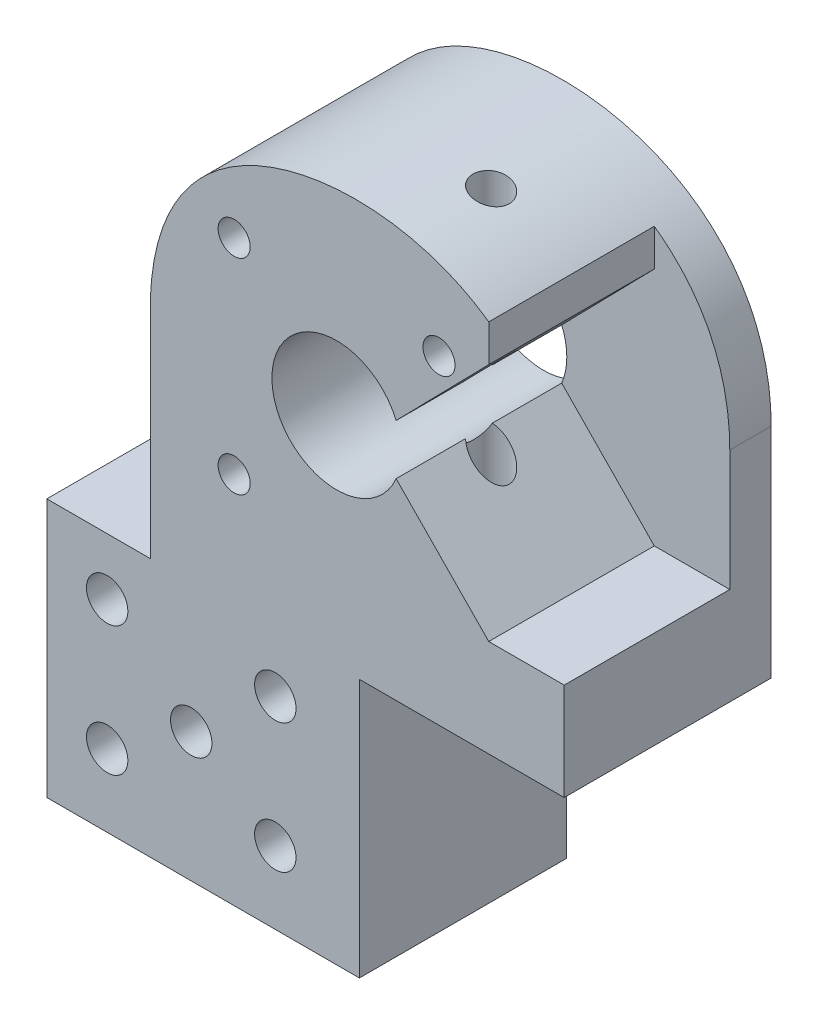
SolidWorks part; units mm, degrees
material "6061-T4 (SS)"
ref_plane "Piano frontale" through (0, 0, 0) normal (0, 0, 1) x (1, 0, 0)
ref_plane "Piano superiore" through (0, 0, 0) normal (0, 1, 0) x (1, 0, 0)
ref_plane "Piano destro" through (0, 0, 0) normal (1, 0, 0) x (0, 0, -1)
sketch "Schizzo1" plane through (0, 0, 0) normal (0, 0, 1) x (1, 0, 0)
  line L0 (28, 46) -> (42, 46) construction
  line L1 (0, 0) -> (30.2052, 0)
  line L2 (30.2052, 25) -> (50, 25)
  line L3 (0, 0) -> (0, 25)
  line L4 (0, 25) -> (10, 25)
  line L5 (10, 25) -> (10, 45.9029)
  line L6 (30.2052, 0) -> (30.2052, 25)
  line L8 (50, 46.0834) -> (50, 25)
  line L9 (28, 46) -> (37.8995, 55.8995) construction
  circle A0 centre (5.8302, 7.0004) radius 2
  circle A1 centre (13.9552, 12.5) radius 2
  circle A2 centre (22.0802, 7.0004) radius 2
  circle A3 centre (22.0802, 19.5004) radius 2
  circle A4 centre (5.8302, 19.5004) radius 2
  circle A5 centre (28, 46) radius 14 construction
  circle A6 centre (37.8995, 55.8995) radius 1.55
  circle A7 centre (28, 46) radius 6.25
  circle A8 centre (37.8995, 36.1005) radius 1.55 construction
  circle A9 centre (18.1005, 36.1005) radius 1.55
  circle A10 centre (18.1005, 55.8995) radius 1.55
  spline S0 degree 3 poles (10, 45.9029) (10, 53.523) (16.6652, 64.7494) (39.9179, 66.5666) (50, 55.4139) (50, 46.0834) knots 0 0 0 0 0.305409 0.638646 1 1 1 1
  point P2 (28, 46)
  point P8 (22.0802, 7.0004)
  point P9 (0, 0)
  point P11 (5.8302, 7.0004)
  point P13 (13.9552, 12.5)
  point P15 (5.8302, 19.5004)
  point P17 (22.0802, 19.5004)
  point P30 (28, 46)
  dimension "D1" = 4
  dimension "D2" = 28
  dimension "D3" = 46
  dimension "D4" = 25
  dimension "D7" = 12.5
  dimension "D8" = 45
  dimension "D9" = 3.1
  dimension "D11" = 12.5
  dimension "D5" = 13.9552
  dimension "D6" = 10
  dimension "D10" = 4
  dimension "D12" = 5.8302
  dimension "D13" = 22.0802
  dimension "D14" = 22.0802
  dimension "D15" = 5.8302
  dimension "D17" = 25
extrude "Estrusione-Estrusione1" add sketch "Schizzo1" against normal blind 20
sketch "Schizzo4" plane through (0, 0, 0) normal (0, 0, 1) x (1, 0, 0)
  line L0 (42.7077, 34.4123) -> (50, 34.4123)
  line L1 (28, 46) -> (53.5435, 46) construction
  line L2 (50, 34.4123) -> (50, 57.5877)
  line L3 (33.4429, 43.8865) -> (33.4429, 48.1135)
  line L4 (42.7077, 57.5877) -> (42.7077, 63.3953)
  line L5 (42.7077, 57.5877) -> (33.4429, 48.1135)
  line L6 (42.7077, 63.3953) -> (50, 63.3953)
  line L7 (50, 63.3953) -> (50, 57.5877)
  line L9 (42.7077, 34.4123) -> (33.4429, 43.8865)
  circle A1 centre (28, 46) radius 5.8388 construction
  point P6 (50, 46)
  point P8 (33.4429, 46)
extrude "Taglio-Estrusione3" cut sketch "Schizzo4" against normal blind 16
sketch "Schizzo5" plane through (0, 25, 0) normal (0, 1, 0) x (1, 0, 0)
  line L0 (40.9379, 8) -> (31.0159, 8) construction
  line L3 (40.9379, 16) -> (40.9379, 0) construction
  line L4 (40.9379, 16) -> (40.9379, 0) construction
  circle A0 centre (34.9379, 8) radius 1.75
  dimension "D1" = 6
  dimension "D2" = 3.5
extrude "Taglio-Estrusione4" cut sketch "Schizzo5" along normal through all
